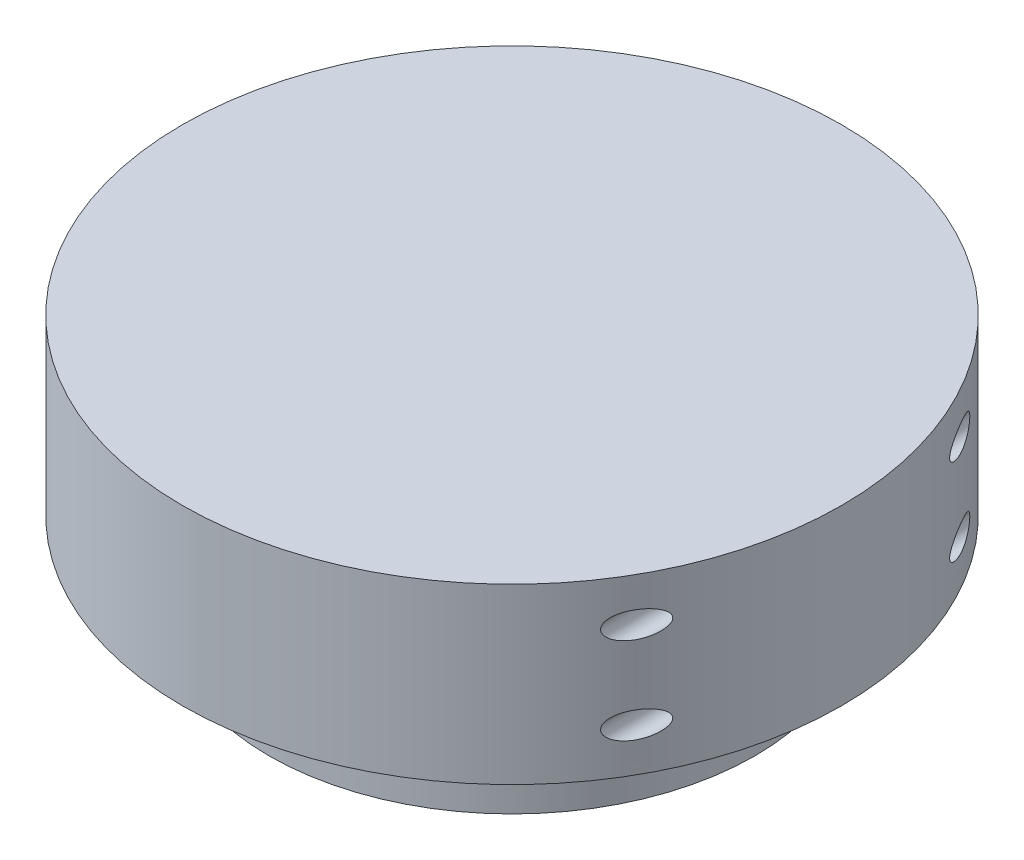
SolidWorks part; units mm, degrees
ref_plane "Front Plane" through (0, 0, 0) normal (0, 0, 1) x (1, 0, 0)
ref_plane "Top Plane" through (0, 0, 0) normal (0, 1, 0) x (1, 0, 0)
ref_plane "Right Plane" through (0, 0, 0) normal (1, 0, 0) x (0, 0, -1)
sketch "Sketch1" plane through (0, 0, 0) normal (0, 1, 0) x (1, 0, 0)
  circle A0 centre (0, 0) radius 38
extrude "Boss-Extrude1" add sketch "Sketch1" along normal blind 20
sketch "Sketch2" plane through (0, 0, 0) normal (0, -1, 0) x (1, 0, 0)
  circle A0 centre (0, 0) radius 22.5
  circle A1 centre (0, 0) radius 28
extrude "Boss-Extrude2" add sketch "Sketch2" along normal blind 10
sketch "Sketch3" plane through (0, 0, 0) normal (0, 0, 1) x (1, 0, 0)
  line L0 (0, 0) -> (0, 31.2829) construction
  circle A0 centre (32.9868, 5) radius 1.5
  circle A1 centre (32.9868, 15) radius 1.5
  circle A2 centre (-32.9868, 5) radius 1.5
  circle A3 centre (-32.9868, 15) radius 1.5
extrude "Cut-Extrude1" cut sketch "Sketch3" against normal through all and the other way through all
